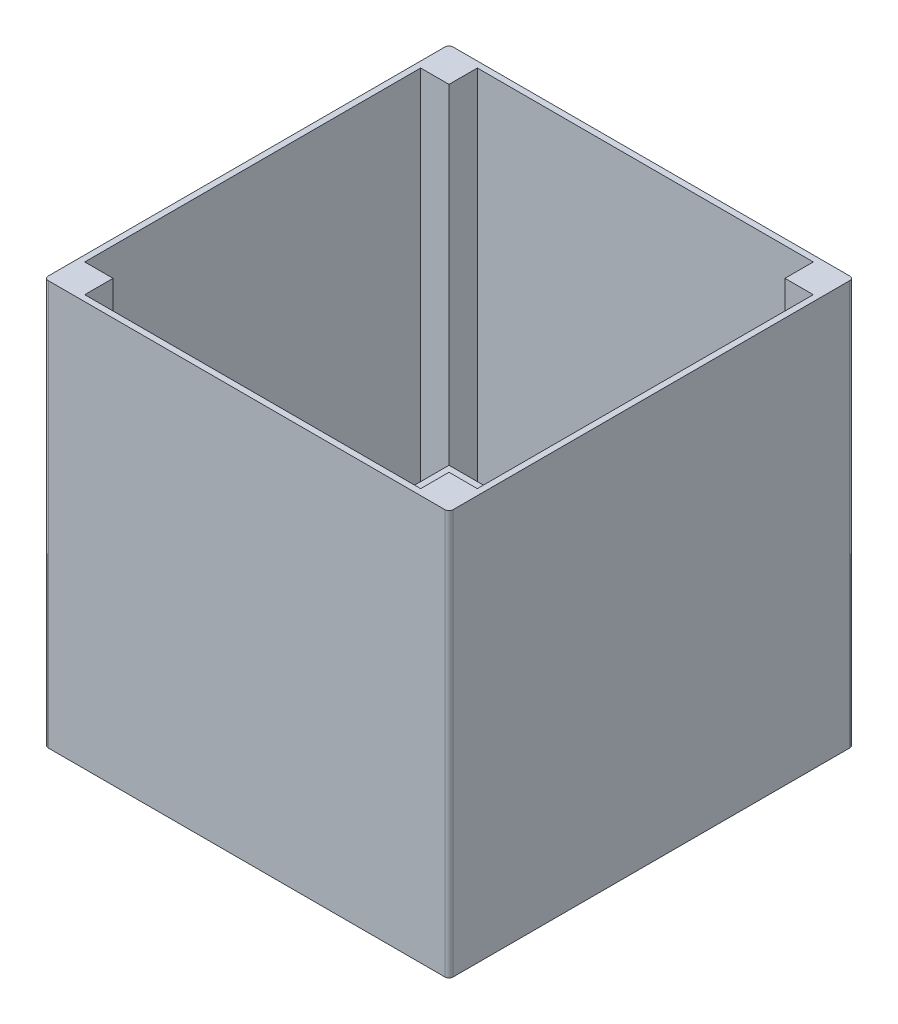
SolidWorks part; units mm, degrees
material "6061-T6 (SS)"
ref_plane "Front Plane" through (0, 0, 0) normal (0, 0, 1) x (1, 0, 0)
ref_plane "Top Plane" through (0, 0, 0) normal (0, 1, 0) x (1, 0, 0)
ref_plane "Right Plane" through (0, 0, 0) normal (1, 0, 0) x (0, 0, -1)
sketch "Sketch1" plane through (0, 0, 0) normal (0, 1, 0) x (1, 0, 0)
  line L0 (-50, 50) -> (-41.5, 50)
  line L1 (-50, -50) -> (50, -50)
  line L2 (-50, -50) -> (-50, 50)
  line L3 (-50, 50) -> (50, 50)
  line L4 (50, -50) -> (50, 50)
  line L5 (-50, -50) -> (50, 50) construction
  line L6 (-50, 50) -> (50, -50) construction
  line L7 (-41.5, 50) -> (-41.5, 41.5)
  line L8 (-41.5, 41.5) -> (-50, 41.5)
  line L9 (0, 50) -> (0, -50) construction
  line L10 (41.5, 41.5) -> (50, 41.5)
  line L11 (41.5, 50) -> (41.5, 41.5)
  line L12 (50, 50) -> (41.5, 50)
  line L13 (41.5, -41.5) -> (41.5, -50)
  line L14 (50, -41.5) -> (41.5, -41.5)
  line L15 (50, -50) -> (50, -41.5)
  line L16 (-50, -50) -> (-50, -41.5)
  line L17 (-50, -41.5) -> (-41.5, -41.5)
  line L18 (-41.5, -41.5) -> (-41.5, -50)
  line L19 (-48.5, 41.5) -> (-48.5, -41.5)
  line L20 (-41.5, -48.5) -> (41.5, -48.5)
  line L21 (48.5, -41.5) -> (48.5, 41.5)
  line L22 (-41.5, 48.5) -> (41.5, 48.5)
  point P0 (0, 0)
  point P28 (0, 0)
  point P29 (-41.5, 41.5)
  point P30 (0, 0)
  point P31 (-41.5, 41.5)
  point P32 (0, 0)
  point P33 (0, 0)
  point P34 (-41.5, 41.5)
  point P35 (0, 0)
  point P36 (0, 0)
  dimension "D1" = 100
  dimension "D2" = 8.5
  dimension "D3" = 1.5
  dimension "D4" = 1.5
  dimension "D5" = 1.5
  dimension "D6" = 1.5
  dimension "D7" = 8.5
extrude "Boss-Extrude2" add sketch "Sketch1" along normal blind 100 contours L3 L11 L10 L4 | L21 L14 L4 L10 | L4 L14 L13 L1 | L20 L18 L1 L13 | L18 L17 L2 L1 | L19 L8 L2 L17 | L8 L7 L0 L2 | L7 L22 L11 L3
ref_plane "Plane1" through (0, 20, 0) normal (0, -1, 0) x (-1, 0, 0)
sketch "Sketch2" plane through (0, 20, 0) normal (0, -1, 0) x (-1, 0, 0)
  line L4 (0, 40) -> (0, -40) construction
  line L5 (-40, -40) -> (40, -40)
  line L6 (-40, -40) -> (-40, 40)
  line L7 (-40, 40) -> (40, 40)
  line L8 (40, -40) -> (40, 40)
  line L9 (-40, -40) -> (40, 40) construction
  line L10 (-40, 40) -> (40, -40) construction
  circle A0 centre (-35, -35) radius 1.6
  circle A1 centre (35, 35) radius 1.6
  circle A2 centre (35, -35) radius 1.6
  circle A3 centre (-35, 35) radius 1.6
  point P0 (0, 0)
  dimension "D3" = 3.2
  dimension "D1" = 80
  dimension "D2" = 5
extrude "Boss-Extrude3" add sketch "Sketch2" along normal blind 2 separate body
fillet "Fillet1" radius 1 4 edges at (50, 50, 50) (-50, 50, 50) (-50, 50, -50) (50, 50, -50)
